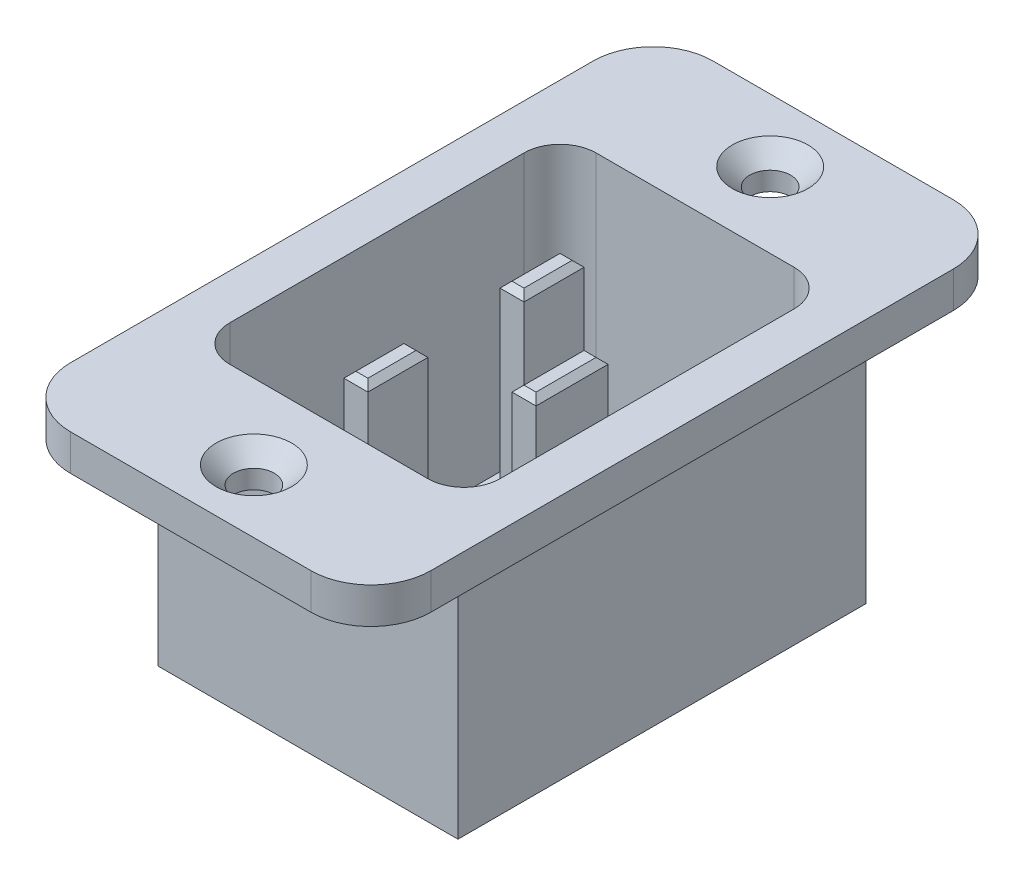
SolidWorks part; units mm, degrees
ref_plane "Front Plane" through (0, 0, 0) normal (0, 0, 1) x (1, 0, 0)
ref_plane "Top Plane" through (0, 0, 0) normal (0, 1, 0) x (1, 0, 0)
ref_plane "Right Plane" through (0, 0, 0) normal (1, 0, 0) x (0, 0, -1)
sketch "Sketch1" plane through (0, 0, 0) normal (0, 1, 0) x (1, 0, 0)
  line L1 (-12.5, 17) -> (12.5, 17)
  line L2 (-12.5, 17) -> (-12.5, -17)
  line L3 (-12.5, -17) -> (12.5, -17)
  line L4 (12.5, 17) -> (12.5, -17)
  line L5 (-12.5, 17) -> (12.5, -17) construction
  line L6 (-12.5, -17) -> (12.5, 17) construction
  point P0 (0, 0)
  dimension "D1" = 25
  dimension "D2" = 34
extrude "Boss-Extrude1" add sketch "Sketch1" against normal blind 20
sketch "Sketch2" plane through (0, 0, 0) normal (0, 1, 0) x (1, 0, 0)
  line L1 (-15, 26.75) -> (15, 26.75)
  line L2 (-15, 26.75) -> (-15, -26.75)
  line L3 (-15, -26.75) -> (15, -26.75)
  line L4 (15, 26.75) -> (15, -26.75)
  line L5 (-15, 26.75) -> (15, -26.75) construction
  line L6 (-15, -26.75) -> (15, 26.75) construction
  point P0 (0, 0)
  dimension "D1" = 53.5
  dimension "D2" = 30
extrude "Boss-Extrude2" add sketch "Sketch2" along normal blind 3
fillet "Fillet1" radius 5 4 edges at (15, 1.5, 26.75) (-15, 1.5, 26.75) (15, 1.5, -26.75) (-15, 1.5, -26.75)
sketch "Sketch3" plane through (0, 3, 0) normal (0, 1, 0) x (1, 0, 0)
  line L0 (0, 0) -> (-4.6665, 0) construction
  line L1 (-11.25, 15.25) -> (11.25, 15.25)
  line L2 (-11.25, 15.25) -> (-11.25, -15.25)
  line L3 (-11.25, -15.25) -> (11.25, -15.25)
  line L4 (11.25, 15.25) -> (11.25, -15.25)
  line L5 (-11.25, 15.25) -> (11.25, -15.25) construction
  line L6 (-11.25, -15.25) -> (11.25, 15.25) construction
  point P0 (0, 0)
  point P6 (0, 21.5)
  point P9 (0, -21.5)
  dimension "D1" = 30.5
  dimension "D2" = 22.5
  dimension "D3" = 21.5
extrude "Cut-Extrude1" cut sketch "Sketch3" against normal blind 22
fillet "Fillet2" radius 3 4 edges at (-11.25, -8, 15.25) (11.25, -8, 15.25) (11.25, -8, -15.25) (-11.25, -8, -15.25)
sketch "Sketch4" plane through (0, -19, 0) normal (0, 1, 0) x (1, 0, 0)
  line L0 (0, 0) -> (-7.7763, 0) construction
  line L1 (3, 3) -> (5, 3)
  line L2 (3, 3) -> (3, -3)
  line L3 (3, -3) -> (5, -3)
  line L4 (5, 3) -> (5, -3)
  line L5 (3, 3) -> (5, -3) construction
  line L6 (3, -3) -> (5, 3) construction
  line L7 (-5, 9) -> (-3, 9)
  line L8 (-5, 9) -> (-5, 4)
  line L9 (-5, 4) -> (-3, 4)
  line L10 (-3, 9) -> (-3, 4)
  line L11 (-5, 9) -> (-3, 4) construction
  line L12 (-5, 4) -> (-3, 9) construction
  line L13 (-5, -4) -> (-3, -9) construction
  line L14 (-5, -9) -> (-3, -4) construction
  line L15 (-3, -9) -> (-3, -4)
  line L16 (-5, -4) -> (-3, -4)
  line L17 (-5, -9) -> (-5, -4)
  line L18 (-5, -9) -> (-3, -9)
  point P0 (4, 0)
  point P5 (-4, 6.5)
  point P17 (-4, -6.5)
  dimension "D1" = 2
  dimension "D2" = 6
  dimension "D3" = 4
  dimension "D4" = 4
  dimension "D5" = 1
  dimension "D6" = 2
  dimension "D7" = 5
extrude "Boss-Extrude3" add sketch "Sketch4" along normal blind 20
chamfer "Chamfer1" distance 0.5 angle 45 12 edges at (4, 1, 3) (3, 1, 0) (4, 1, -3) (5, 1, 0) (-4, 1, 4) (-3, 1, 6.5) (-4, 1, 9) (-5, 1, 6.5) (-4, 1, -4) (-5, 1, -6.5) (-4, 1, -9) (-3, 1, -6.5)
hole_wizard "CSK for M3 Flat Head Machine Screw1" positions "3DSketch1" profile "Sketch5" countersink size "M3" standard "ANSI Metric"
sketch3d "3DSketch1"
  point P0 (0, 3, -21.5)
  point P3 (0, 3, 21.5)
sketch "Sketch5" plane through (0, 3, -21.5) normal (1, 0, 0) x (0, 0, 1)
  line L0 (0, 0) -> (0, 4.0215)
  line L1 (0, 4.0215) -> (1.7, 3)
  line L2 (1.7, 3) -> (1.7, 1.45)
  line L3 (1.7, 1.45) -> (3.15, 0)
  line L5 (3.15, 0) -> (0, 0)
  line L6 (-1.7, 1.45) -> (-3.15, 0) construction
  line L10 (0, 4.0215) -> (-1.7, 3) construction
  line L11 (0, -6.35) -> (0, 107.95) construction
  dimension "Hole Dia." = 3.4
  dimension "Hole Depth" = 3
  dimension "Near C'Sink Dia." = 6.3
  dimension "Near C'Sink Angle" = 90
  dimension "Drill Angle" = 118
